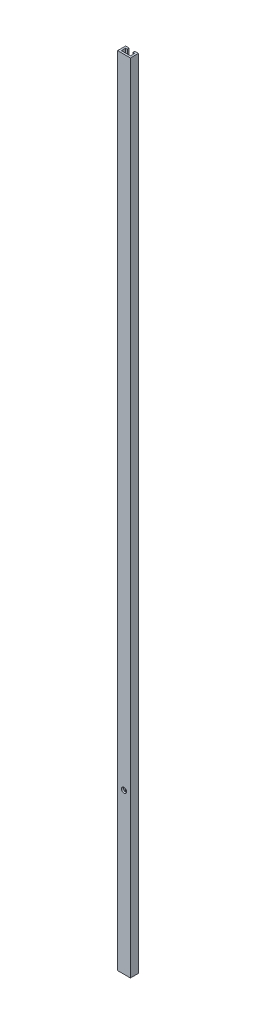
SolidWorks part; units mm, degrees
ref_plane "前视基准面" through (0, 0, 0) normal (0, 0, 1) x (1, 0, 0)
ref_plane "上视基准面" through (0, 0, 0) normal (0, 1, 0) x (1, 0, 0)
ref_plane "右视基准面" through (0, 0, 0) normal (1, 0, 0) x (0, 0, -1)
sketch "草图1" plane through (0, 0, 0) normal (0, 1, 0) x (1, 0, 0)
  line L0 (0, -5) -> (8, -5)
  line L1 (8, -5) -> (8, 0)
  line L2 (8, 0) -> (5.75, 0)
  line L3 (5.75, 0) -> (5.75, -1.15)
  line L4 (5.75, -1.15) -> (6.85, -1.15)
  line L5 (6.85, -1.15) -> (6.85, -3.85)
  line L6 (6.85, -3.85) -> (1.15, -3.85)
  line L7 (1.15, -3.85) -> (1.15, -1.15)
  line L8 (1.15, -1.15) -> (2.25, -1.15)
  line L9 (2.25, -1.15) -> (2.25, 0)
  line L10 (2.25, 0) -> (0, 0)
  line L11 (0, 0) -> (0, -5)
  line L12 (4, -3.85) -> (4, -5) construction
  line L13 (2.25, 0) -> (5.75, 0) construction
  line L14 (4, 0) -> (4, -3.85) construction
  dimension "D1" = 5
  dimension "D2" = 8
  dimension "D3" = 1.15
  dimension "D4" = 1.15
  dimension "D5" = 1.15
  dimension "D6" = 3.5
  dimension "D7" = 5.7
extrude "凸台-拉伸1" add sketch "草图1" along normal blind 500
sketch "草图2" plane through (0, 0, 5) normal (0, 0, 1) x (1, 0, 0)
  line L0 (0, 0) -> (8, 0) construction
  line L1 (4, 100) -> (4, 0) construction
  circle A0 centre (4, 100) radius 1.6
  point P4 (4, 0)
  dimension "D2" = 3.2
  dimension "D1" = 100
extrude "切除-拉伸1" cut sketch "草图2" against normal up to surface (1.15 mm away) up to face at (4, 250, 3.85)
